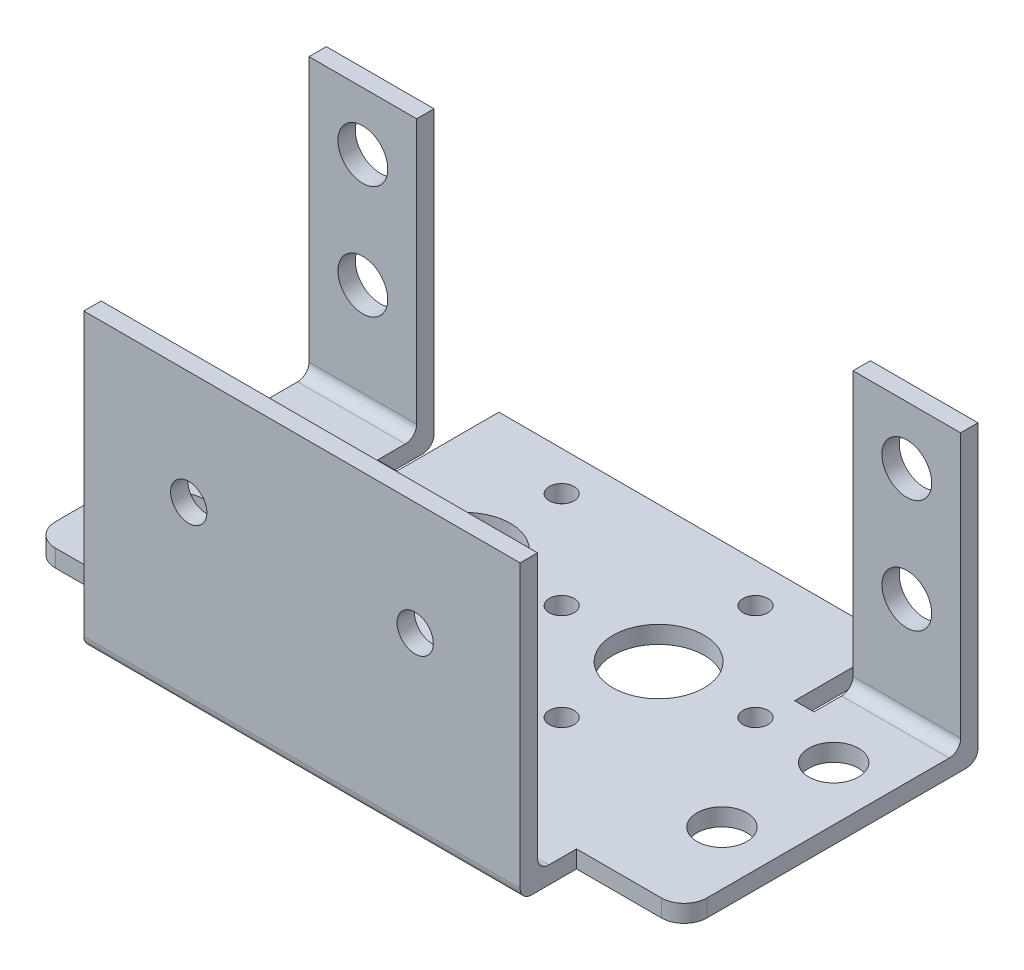
SolidWorks part; units mm, degrees
material "1060 Alloy"
ref_plane "Front" through (0, 0, 0) normal (0, 0, 1) x (1, 0, 0)
ref_plane "Top" through (0, 0, 0) normal (0, 1, 0) x (1, 0, 0)
ref_plane "Right" through (0, 0, 0) normal (1, 0, 0) x (0, 0, -1)
sketch "Sketch1" plane through (0, 0, 0) normal (0, 1, 0) x (1, 0, 0)
  line L0 (-28.575, 17.36) -> (28.575, 17.36)
  line L1 (28.575, 17.36) -> (28.575, -17.36)
  line L2 (28.575, -17.36) -> (-28.575, -17.36)
  line L3 (-28.575, -17.36) -> (-28.575, 17.36)
  line L4 (0, 17.36) -> (0, -17.36) construction
  point P6 (0, 0)
  dimension "D1" = 57.15
  dimension "D2" = 34.72
extrude "Boss-Extrude1" add sketch "Sketch1" along normal blind 1.524
ref_plane "Plane1" through (0, 1.524, 0) normal (0, 1, 0) x (1, 0, 0)
sketch "Sketch2" plane through (0, 1.524, 0) normal (0, 1, 0) x (1, 0, 0)
  line L0 (28.575, -17.36) -> (28.575, -12.41)
  line L1 (28.575, -17.36) -> (28.575, 17.36) construction
  line L2 (28.575, -12.41) -> (19.135, -12.41)
  line L3 (19.135, -12.41) -> (19.135, -17.36)
  line L4 (-28.575, -17.36) -> (28.575, -17.36) construction
  line L5 (19.135, -17.36) -> (28.575, -17.36)
  line L6 (28.575, 17.36) -> (17.445, 17.36)
  line L7 (28.575, 17.36) -> (-28.575, 17.36) construction
  line L8 (17.445, 17.36) -> (17.445, 8.41)
  line L9 (17.445, 8.41) -> (19.135, 8.41)
  line L10 (19.135, 13.36) -> (28.575, 13.36)
  line L11 (19.135, 8.41) -> (19.135, -17.36) construction
  line L12 (19.135, 8.41) -> (19.135, 13.36)
  line L13 (28.575, 13.36) -> (28.575, 17.36)
  dimension "D2" = 4.95
  dimension "D3" = 11.13
  dimension "D4" = 4.95
  dimension "D5" = 1.69
  dimension "D6" = 8.95
extrude "Cut-Extrude1" cut sketch "Sketch2" against normal mid plane 10
mirror "Mirror1" about plane through (0, 0, 0) normal (1, 0, 0) of "Cut-Extrude1"
sketch "Sketch3" plane through (0, 1.524, 0) normal (0, 1, 0) x (1, 0, 0)
  line L0 (23.855, 13.36) -> (23.855, -12.41) construction
  line L1 (28.575, 13.36) -> (19.135, 13.36) construction
  line L2 (19.135, -12.41) -> (28.575, -12.41) construction
  circle A0 centre (23.855, -4.38) radius 2.1844
  circle A1 centre (23.855, 5.42) radius 2.1844
  dimension "D1" = 4.3688
  dimension "D2" = 9.8
  dimension "D3" = 8.03
extrude "Cut-Extrude2" cut sketch "Sketch3" against normal mid plane 10
mirror "Mirror2" about plane through (0, 0, 0) normal (1, 0, 0) of "Cut-Extrude2"
sketch "Sketch4" plane through (0, 1.524, 0) normal (0, 1, 0) x (1, 0, 0)
  line L0 (-19.135, -17.36) -> (19.135, -17.36)
  line L1 (19.135, -15.836) -> (-19.135, -15.836)
  line L2 (19.135, -17.36) -> (19.135, -12.41) construction
  line L3 (-19.135, -17.36) -> (-19.135, -12.41) construction
  line L4 (-19.135, -15.836) -> (-19.135, -17.36)
  line L5 (-28.575, 13.36) -> (-19.135, 13.36)
  line L6 (-19.135, 13.36) -> (-19.135, 11.836)
  line L7 (-19.135, 13.36) -> (-19.135, 8.41) construction
  line L8 (-19.135, 11.836) -> (-28.575, 11.836)
  line L9 (-28.575, 13.36) -> (-28.575, -12.41) construction
  line L10 (-28.575, 11.836) -> (-28.575, 13.36)
  line L11 (0, 17.36) -> (0, -17.36) construction
  line L12 (17.445, 17.36) -> (-17.445, 17.36) construction
  line L13 (28.575, 11.836) -> (28.575, 13.36)
  line L14 (19.135, 11.836) -> (28.575, 11.836)
  line L15 (19.135, 13.36) -> (19.135, 11.836)
  line L16 (28.575, 13.36) -> (19.135, 13.36)
  line L17 (19.135, -15.836) -> (19.135, -17.36)
  dimension "D1" = 1.524
  dimension "D2" = 1.524
extrude "Boss-Extrude2" add sketch "Sketch4" along normal blind 24.2
ref_plane "Plane2" through (0, 0, 17.36) normal (0, 0, 1) x (1, 0, 0)
sketch "Sketch5" plane through (0, 0, 17.36) normal (0, 0, 1) x (1, 0, 0)
  line L0 (0, 25.724) -> (0, 0) construction
  line L1 (-19.135, 25.724) -> (19.135, 25.724) construction
  circle A0 centre (-9.93, 15.794) radius 1.59
  circle A1 centre (9.93, 15.794) radius 1.59
  dimension "D1" = 3.18
  dimension "D2" = 9.93
  dimension "D3" = 19.86
extrude "Cut-Extrude3" cut sketch "Sketch5" against normal mid plane 24.2
sketch "Sketch6" plane through (0, 1.524, 0) normal (0, 1, 0) x (1, 0, 0)
  line L0 (0, 17.36) -> (0, -17.36) construction
  line L1 (17.445, 17.36) -> (-17.445, 17.36) construction
  line L2 (-14.1482, -17.36) -> (14.1482, -17.36) construction
  circle A0 centre (0, 5.42) radius 1.09
  dimension "D1" = 2.18
  dimension "D2" = 11.94
extrude "Cut-Extrude4" cut sketch "Sketch6" against normal blind 24.2
sketch "Sketch7" plane through (0, 1.524, 0) normal (0, 1, 0) x (1, 0, 0)
  circle A0 centre (-8.5, 5.42) radius 4
  circle A1 centre (0, 5.42) radius 1.09 construction
  dimension "D2" = 8
  dimension "D3" = 8.5
  dimension "D1" = 8.5
extrude "Cut-Extrude5" cut sketch "Sketch7" against normal blind 24.2
sketch "Sketch8" plane through (0, 1.524, 0) normal (0, 1, 0) x (1, 0, 0)
  circle A0 centre (-8.5, 13.92) radius 1.09
  circle A1 centre (0, 5.42) radius 1.09 construction
  circle A2 centre (-8.5, 5.42) radius 4 construction
  dimension "D1" = 8.5
  dimension "D2" = 8.5
extrude "Cut-Extrude6" cut sketch "Sketch8" against normal blind 24.2
pattern_circular "CirPattern1" count 4 over 360 about axis through (-8.5, 0, -5.42) along (0, 1, 0) skipping 3 of "Cut-Extrude6"
mirror "Mirror3" about plane through (0, 0, 0) normal (1, 0, 0) of "Cut-Extrude5", "Cut-Extrude6", "CirPattern1"
ref_plane "Plane3" through (0, 0, -11.836) normal (0, 0, 1) x (1, 0, 0)
sketch "Sketch9" plane through (0, 0, -11.836) normal (0, 0, 1) x (1, 0, 0)
  line L0 (-23.855, 20.644) -> (-23.855, 10.734) construction
  line L1 (0, 0) -> (0, 25.724) construction
  line L2 (-19.135, 25.724) -> (19.135, 25.724) construction
  line L3 (23.855, 20.644) -> (23.855, 10.734) construction
  line L4 (-28.575, 25.724) -> (-19.135, 25.724) construction
  circle A0 centre (-23.855, 20.644) radius 2.1844
  circle A1 centre (-23.855, 10.734) radius 2.1844
  circle A2 centre (23.855, 10.734) radius 2.1844
  circle A3 centre (23.855, 20.644) radius 2.1844
  dimension "D1" = 4.3688
  dimension "D3" = 5.08
  dimension "D4" = 9.91
  dimension "D2" = 47.71
extrude "Cut-Extrude7" cut sketch "Sketch9" against normal mid plane 24.2
fillet "Fillet1" radius 2 2 edges at (-28.575, 0.762, 12.41) (28.575, 0.762, 12.41)
fillet "Fillet2" radius 1 6 edges at (0, 0, 17.36) (23.855, 0, -13.36) (-23.855, 0, -13.36) (23.855, 1.524, -11.836) (-23.855, 1.524, -11.836)
